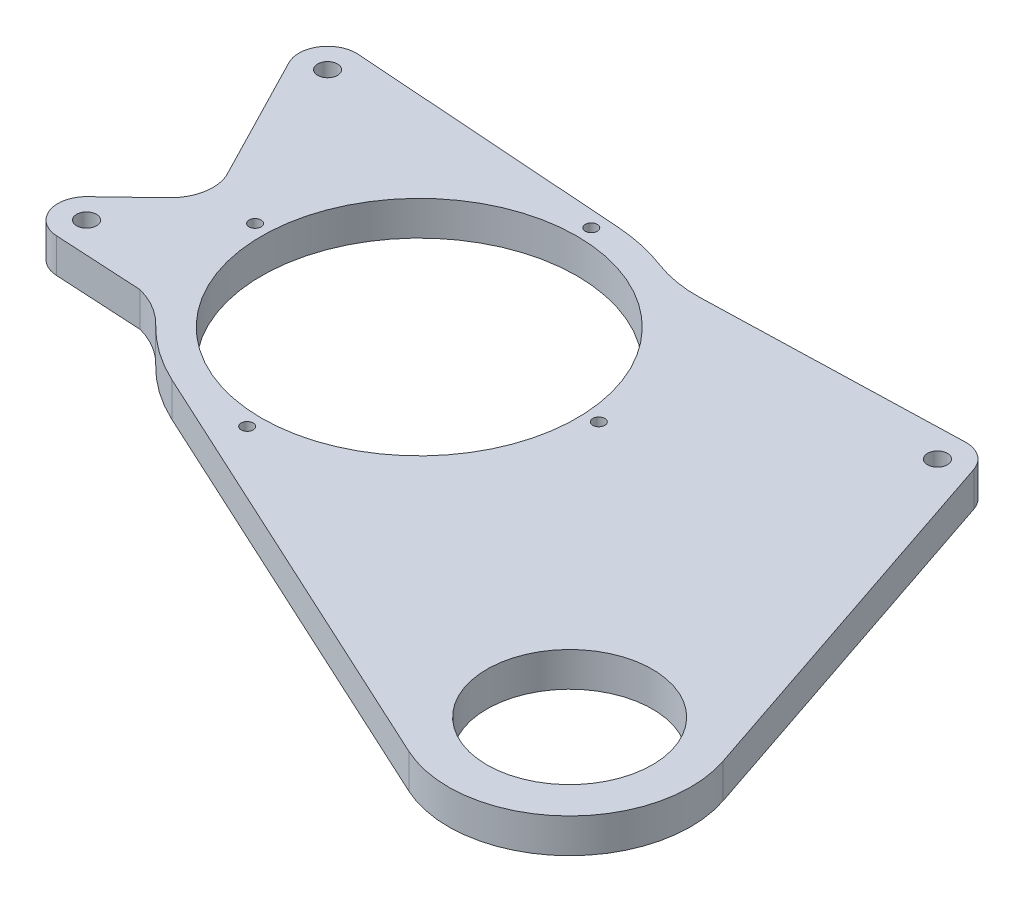
SolidWorks part; units mm, degrees
material "7075-T6 (SN)"
ref_plane "X-Y Datum" through (0, 0, 0) normal (0, 0, 1) x (1, 0, 0)
ref_plane "X-Z Datum" through (0, 0, 0) normal (0, 1, 0) x (1, 0, 0)
ref_plane "Y-Z Datum" through (0, 0, 0) normal (1, 0, 0) x (0, 0, -1)
sketch "Sketch1" plane through (0, 0, 0) normal (0, 1, 0) x (1, 0, 0)
  line L0 (-455.0302, -196.5692) -> (-601.2693, -129.0289)
  line L1 (-399.9958, -147.173) -> (-442.257, -21.6619)
  line L2 (-663.9188, -4.4766) -> (-570.935, -11.0638)
  line L3 (-568.96, 0) -> (-457.2, 0) construction
  line L4 (-685.8, 0) -> (-568.96, 0) construction
  line L5 (-685.8, -104.2174) -> (-685.8, 0) construction
  line L6 (-685.8, -104.2174) -> (-575.31, -72.8215) construction
  line L7 (-575.31, -72.8215) -> (-438.15, -160.02) construction
  line L8 (-685.8, 0) -> (-575.31, -72.8215) construction
  line L9 (-575.31, -72.8215) -> (-457.2, 0) construction
  line L10 (-673.0578, -18.3429) -> (-650.8058, -61.4992)
  line L11 (-667.9407, -90.3817) -> (-654.3431, -77.4145)
  line L12 (-661.8912, -106.7853) -> (-632.4025, -108.4098)
  line L13 (-451.5613, -15.1805) -> (-537.1096, -17.6715)
  circle A0 centre (-661.3672, -97.2748) radius 9.525 construction
  circle A1 centre (-664.5919, -13.9778) radius 9.525 construction
  circle A2 centre (-451.2841, -24.7015) radius 9.525 construction
  circle A3 centre (-661.3672, -97.2748) radius 3.3
  circle A4 centre (-664.5919, -13.9778) radius 3.3
  circle A5 centre (-451.2841, -24.7015) radius 3.3
  arc A6 (-632.4025, -108.4098) -> (-619.8429, -115.8328) centre (-639.5866, -134.9019) cw
  arc A7 (-619.8429, -115.8328) -> (-601.2693, -129.0289) centre (-575.31, -72.8215) ccw
  arc A8 (-654.3431, -77.4145) -> (-650.8058, -61.4992) centre (-663.9808, -66.9217) ccw
  arc A11 (-451.5613, -15.1805) -> (-442.257, -21.6619) centre (-451.2841, -24.7015) cw
  arc A12 (-455.0302, -196.5692) -> (-399.9958, -147.173) centre (-438.15, -160.02) ccw
  circle A13 centre (-438.15, -160.02) radius 27.5
  circle A17 centre (-575.31, -72.8215) radius 61.9125 construction
  circle A18 centre (-575.31, -72.8215) radius 52.3875
  arc A19 (-575.31, -17.6715) -> (-575.31, -13.6715) centre (-575.31, -15.6715) ccw
  arc A20 (-575.31, -13.6715) -> (-575.31, -17.6715) centre (-575.31, -15.6715) ccw
  circle A21 centre (-632.4025, -70.2575) radius 2
  arc A22 (-518.2175, -72.2575) -> (-518.2175, -68.2575) centre (-518.2175, -70.2575) ccw
  arc A23 (-518.2175, -68.2575) -> (-518.2175, -72.2575) centre (-518.2175, -70.2575) ccw
  arc A24 (-575.31, -131.9715) -> (-575.31, -127.9715) centre (-575.31, -129.9715) ccw
  arc A25 (-575.31, -127.9715) -> (-575.31, -131.9715) centre (-575.31, -129.9715) ccw
  circle A26 centre (-685.8, -104.2174) radius 12.7 construction
  circle A27 centre (-685.8, 0) radius 12.7 construction
  circle A28 centre (-457.2, 0) radius 12.7 construction
  circle A29 centre (-438.15, -160.02) radius 40.259 construction
  arc A30 (-661.8912, -106.7853) -> (-667.9407, -90.3817) centre (-661.3672, -97.2748) cw
  arc A31 (-673.0578, -18.3429) -> (-663.9188, -4.4766) centre (-664.5919, -13.9778) cw
  arc A34 (-537.1096, -17.6715) -> (-553.3217, -14.9451) centre (-538.3667, 24.4186) cw
  arc A36 (-570.935, -11.0638) -> (-553.3217, -14.9451) centre (-575.31, -72.8215) cw
  dimension "D7" = 25.4
  dimension "D10" = 123.825
  dimension "D11" = 104.775
  dimension "D12" = 55
  dimension "D13" = 80.518
  dimension "D15" = 4
  dimension "D18" = 57.0925
  dimension "D24" = 19.05
  dimension "D25" = 6.6
  dimension "D26" = 7.0241
  dimension "D29" = 14.2472
  dimension "D33" = 27.4489
  dimension "D34" = 42.1088
  dimension "D1" = 685.8
  dimension "D2" = 116.84
  dimension "D3" = 228.6
  dimension "D4" = 19.05
  dimension "D5" = 160.02
  dimension "D6" = 104.2174
  dimension "D8" = 72.8215
  dimension "D9" = 110.49
  dimension "D14" = 114.864
  dimension "D16" = 57.0925
  dimension "D17" = 2.564
  dimension "D19" = 57.15
  dimension "D20" = 57.15
  dimension "D21" = 25.4
  dimension "D22" = 25.4
  dimension "D23" = 25.4
  dimension "D27" = 5.9159
  dimension "D28" = 12.9672
  dimension "D30" = 30.3531
  dimension "D31" = 29.4887
  dimension "D32" = 11.1351
  dimension "D35" = 15.1805
  dimension "D36" = 3.8814
extrude "Boss-Extrude1" add sketch "Sketch1" along normal blind 11.43
